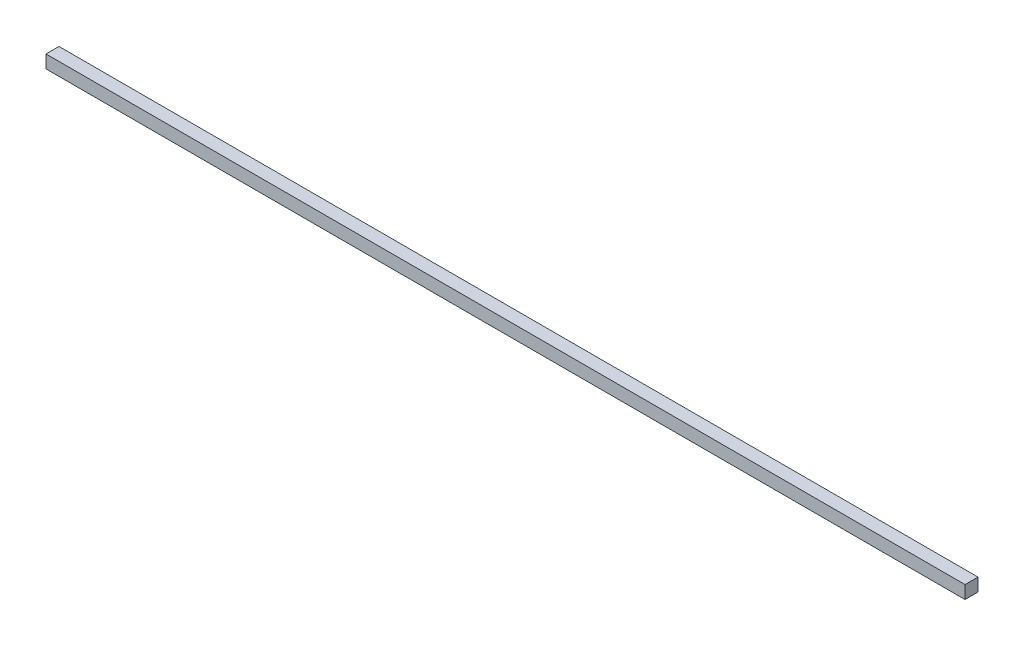
SolidWorks part; units mm, degrees
material "Balsa"
ref_plane "Front Plane" through (0, 0, 0) normal (0, 0, 1) x (1, 0, 0)
ref_plane "Top Plane" through (0, 0, 0) normal (0, 1, 0) x (1, 0, 0)
ref_plane "Right Plane" through (0, 0, 0) normal (1, 0, 0) x (0, 0, -1)
sketch "Sketch1" plane through (0, 0, 0) normal (0, 0, 1) x (1, 0, 0)
  line L1 (0, 0) -> (245.11, 0)
  line L2 (0, 0) -> (0, 3.175)
  line L3 (0, 3.175) -> (245.11, 3.175)
  line L4 (245.11, 0) -> (245.11, 3.175)
  dimension "D1" = 245.11
  dimension "D2" = 3.175
extrude "Boss-Extrude1" add sketch "Sketch1" along normal blind 3.175
sketch "Sketch2" plane through (0, 0, 3.175) normal (0, 0, 1) x (1, 0, 0)
  line L7 (245.11, 3.175) -> (0, 3.175) construction
  line L8 (245.11, 0) -> (224.79, 0)
  line L9 (245.11, 0) -> (245.11, 3.175)
  line L10 (245.11, 3.175) -> (224.79, 3.175)
  line L11 (224.79, 0) -> (224.79, 3.175)
  dimension "D1" = 20.32
extrude "Cut-Extrude1" cut sketch "Sketch2" against normal through all
